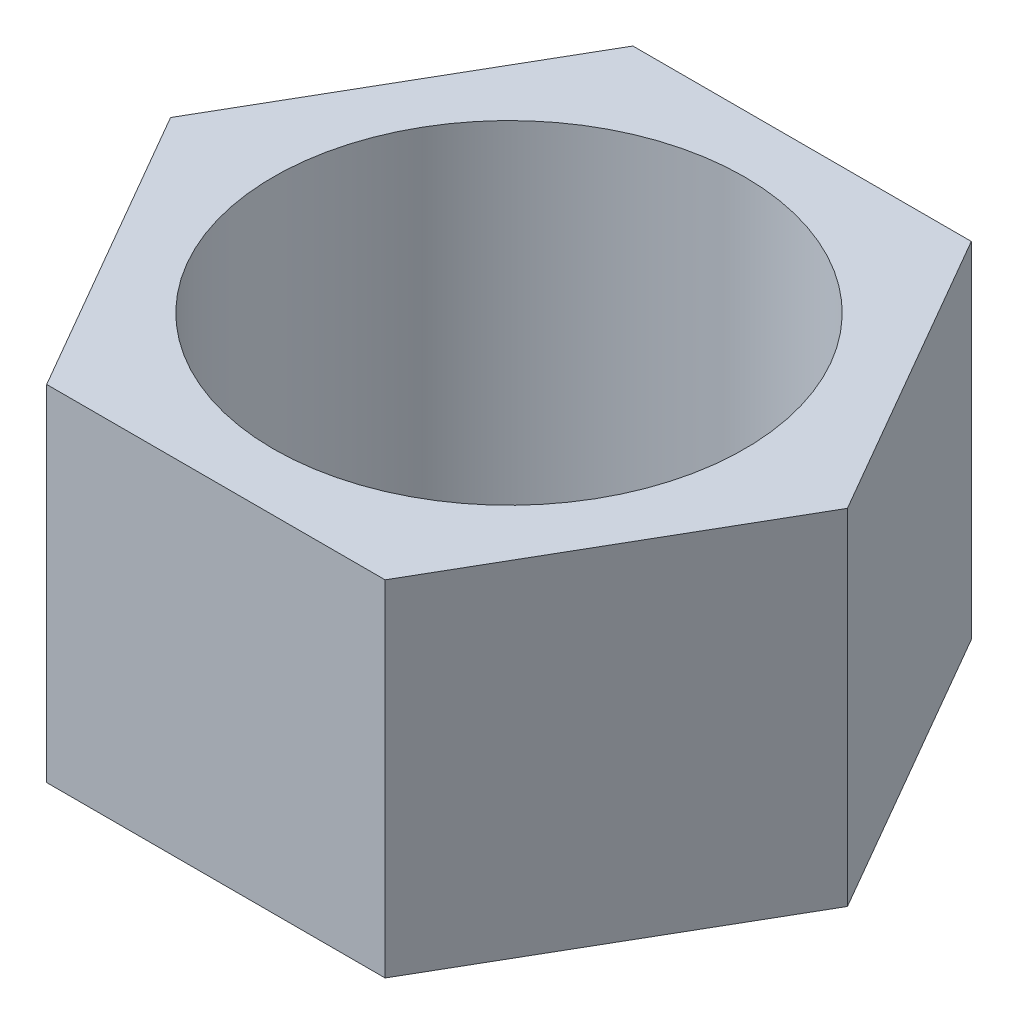
SolidWorks part; units mm, degrees
material "Alloy Steel"
ref_plane "Front Plane" through (0, 0, 0) normal (0, 0, 1) x (1, 0, 0)
ref_plane "Top Plane" through (0, 0, 0) normal (0, 1, 0) x (1, 0, 0)
ref_plane "Right Plane" through (0, 0, 0) normal (1, 0, 0) x (0, 0, -1)
sketch "Sketch1" plane through (0, 0, 0) normal (0, 1, 0) x (1, 0, 0)
  line L1 (7.479, 0) -> (3.7395, 6.477)
  line L2 (3.7395, 6.477) -> (-3.7395, 6.477)
  line L3 (-3.7395, 6.477) -> (-7.479, 0)
  line L4 (-7.479, 0) -> (-3.7395, -6.477)
  line L5 (-3.7395, -6.477) -> (3.7395, -6.477)
  line L6 (3.7395, -6.477) -> (7.479, 0)
  circle A0 centre (0, 0) radius 6.477 construction
  circle A1 centre (0, 0) radius 5.207
  dimension "D1" = 10.414
  dimension "D2" = 12.954
extrude "Boss-Extrude1" add sketch "Sketch1" along normal blind 7.62
